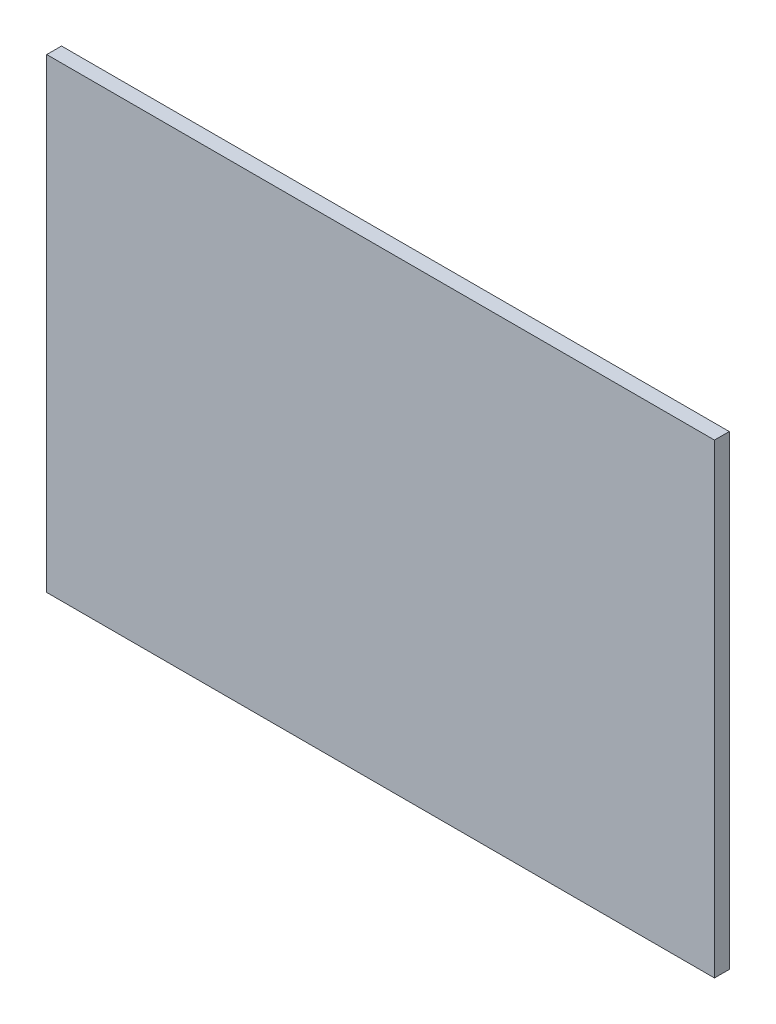
SolidWorks part; units mm, degrees
ref_plane "Front Plane" through (0, 0, 0) normal (0, 0, 1) x (1, 0, 0)
ref_plane "Top Plane" through (0, 0, 0) normal (0, 1, 0) x (1, 0, 0)
ref_plane "Right Plane" through (0, 0, 0) normal (1, 0, 0) x (0, 0, -1)
sketch "Sketch1" plane through (0, 0, 0) normal (0, 0, 1) x (1, 0, 0)
  line L1 (-430, -300) -> (430, -300)
  line L2 (-430, -300) -> (-430, 300)
  line L3 (-430, 300) -> (430, 300)
  line L4 (430, -300) -> (430, 300)
  line L5 (-430, -300) -> (430, 300) construction
  line L6 (-430, 300) -> (430, -300) construction
  point P0 (0, 0)
  dimension "D1" = 860
  dimension "D2" = 600
extrude "Boss-Extrude1" add sketch "Sketch1" along normal blind 19.05
